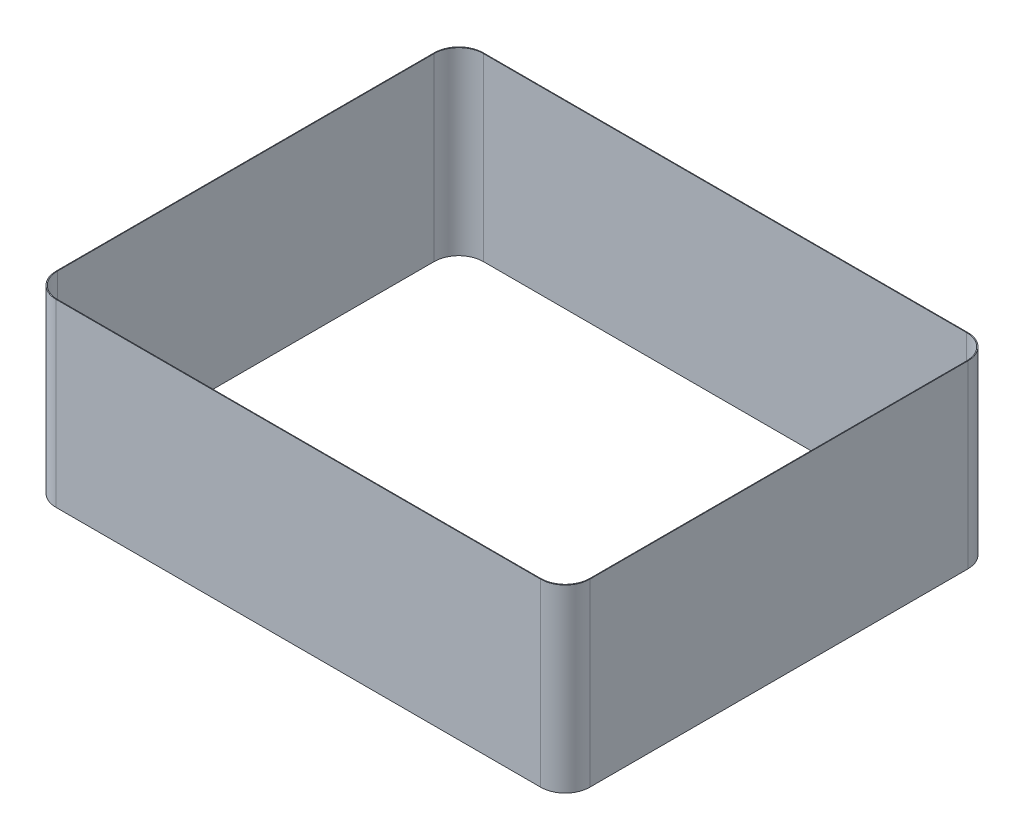
SolidWorks part; units mm, degrees
material "PET"
ref_plane "Front Plane" through (0, 0, 0) normal (0, 0, 1) x (1, 0, 0)
ref_plane "Top Plane" through (0, 0, 0) normal (0, 1, 0) x (1, 0, 0)
ref_plane "Right Plane" through (0, 0, 0) normal (1, 0, 0) x (0, 0, -1)
sketch "Sketch1" plane through (0, 0, 0) normal (0, 1, 0) x (1, 0, 0)
  line L1 (-93.9165, -82.804) -> (93.9165, -82.804)
  line L2 (-103.4415, -73.279) -> (-103.4415, 73.279)
  line L3 (-93.9165, 82.804) -> (93.9165, 82.804)
  line L4 (103.4415, -73.279) -> (103.4415, 73.279)
  line L5 (-103.4415, -82.804) -> (103.4415, 82.804) construction
  line L6 (-103.4415, 82.804) -> (103.4415, -82.804) construction
  line L7 (-93.6625, -82.55) -> (93.6625, -82.55)
  line L8 (-103.1875, -73.025) -> (-103.1875, 73.025)
  line L9 (-93.6625, 82.55) -> (93.6625, 82.55)
  line L10 (103.1875, -73.025) -> (103.1875, 73.025)
  line L11 (-103.1875, -82.55) -> (103.1875, 82.55) construction
  line L12 (-103.1875, 82.55) -> (103.1875, -82.55) construction
  arc A0 (93.9165, 82.804) -> (103.4415, 73.279) centre (93.9165, 73.279) cw
  arc A1 (93.6625, 82.55) -> (103.1875, 73.025) centre (93.6625, 73.025) cw
  arc A2 (93.6625, -82.55) -> (103.1875, -73.025) centre (93.6625, -73.025) ccw
  arc A3 (93.9165, -82.804) -> (103.4415, -73.279) centre (93.9165, -73.279) ccw
  arc A4 (-93.9165, -82.804) -> (-103.4415, -73.279) centre (-93.9165, -73.279) cw
  arc A5 (-93.6625, -82.55) -> (-103.1875, -73.025) centre (-93.6625, -73.025) cw
  arc A6 (-103.4415, 73.279) -> (-93.9165, 82.804) centre (-93.9165, 73.279) cw
  arc A7 (-103.1875, 73.025) -> (-93.6625, 82.55) centre (-93.6625, 73.025) cw
  point P0 (0, 0)
  point P6 (0, 0)
  dimension "D5" = 9.525
  dimension "D1" = 206.375
  dimension "D2" = 165.1
  dimension "D3" = 0.254
  dimension "D4" = 0.254
extrude "Boss-Extrude1" add sketch "Sketch1" along normal blind 69.85
